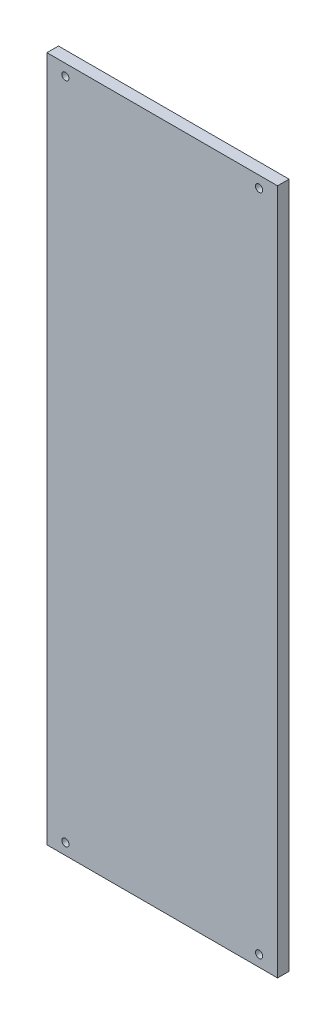
SolidWorks part; units mm, degrees
material "1060 Alloy"
ref_plane "Front Plane" through (0, 0, 0) normal (0, 0, 1) x (1, 0, 0)
ref_plane "Top Plane" through (0, 0, 0) normal (0, 1, 0) x (1, 0, 0)
ref_plane "Right Plane" through (0, 0, 0) normal (1, 0, 0) x (0, 0, -1)
sketch "Sketch1" plane through (0, 0, 0) normal (0, 0, 1) x (1, 0, 0)
  line L1 (-127, 377.825) -> (127, 377.825)
  line L2 (-127, 377.825) -> (-127, -377.825)
  line L3 (-127, -377.825) -> (127, -377.825)
  line L4 (127, 377.825) -> (127, -377.825)
  line L5 (-127, 377.825) -> (127, -377.825) construction
  line L6 (-127, -377.825) -> (127, 377.825) construction
  point P0 (0, 0)
  dimension "D1" = 254
  dimension "D2" = 755.65
extrude "Boss-Extrude1" add sketch "Sketch1" along normal blind 12.7
sketch "Sketch4" plane through (0, 0, 0) normal (0, 0, -1) x (-1, 0, 0)
  line L0 (-127, 377.825) -> (127, 377.825) construction
  line L1 (-127, -377.825) -> (-127, 377.825) construction
  line L2 (127, 377.825) -> (127, -377.825) construction
  point P0 (-106.68, 365.379)
  point P1 (106.68, 365.379)
  dimension "D1" = 12.446
  dimension "D2" = 12.446
  dimension "D3" = 20.32
  dimension "D4" = 20.32
sketch "Sketch5" plane through (0, 0, 0) normal (0, 0, -1) x (-1, 0, 0)
  line L0 (127, -377.825) -> (-127, -377.825) construction
  line L1 (-127, -377.825) -> (-127, 377.825) construction
  line L2 (127, 377.825) -> (127, -377.825) construction
  point P0 (-106.68, -365.379)
  point P1 (106.68, -365.379)
  dimension "D1" = 12.446
  dimension "D2" = 20.32
  dimension "D3" = 12.446
  dimension "D4" = 20.32
hole_wizard "5/16 (0.3125) Diameter Hole1" positions "Sketch6" profile "Sketch7" hole size "5/16" standard "ANSI Inch" end condition through all
sketch "Sketch6" plane through (0, 0, 0) normal (0, 0, -1) x (-1, 0, 0)
  point P0 (-106.68, 365.379)
  point P3 (106.68, 365.379)
  point P6 (-106.68, -365.379)
  point P9 (106.68, -365.379)
sketch "Sketch7" plane through (106.68, 365.379, 0) normal (1, 0, 0) x (0, 1, 0)
  line L0 (0, 0) -> (0, 12.7)
  line L1 (0, 12.7) -> (3.9687, 12.7)
  line L2 (3.9687, 12.7) -> (3.9687, 0)
  line L5 (3.9687, 0) -> (0, 0)
  line L11 (0, -6.35) -> (0, 107.95) construction
  dimension "Thru Hole Dia." = 7.9375
  dimension "Thru Hole Depth" = 12.7
